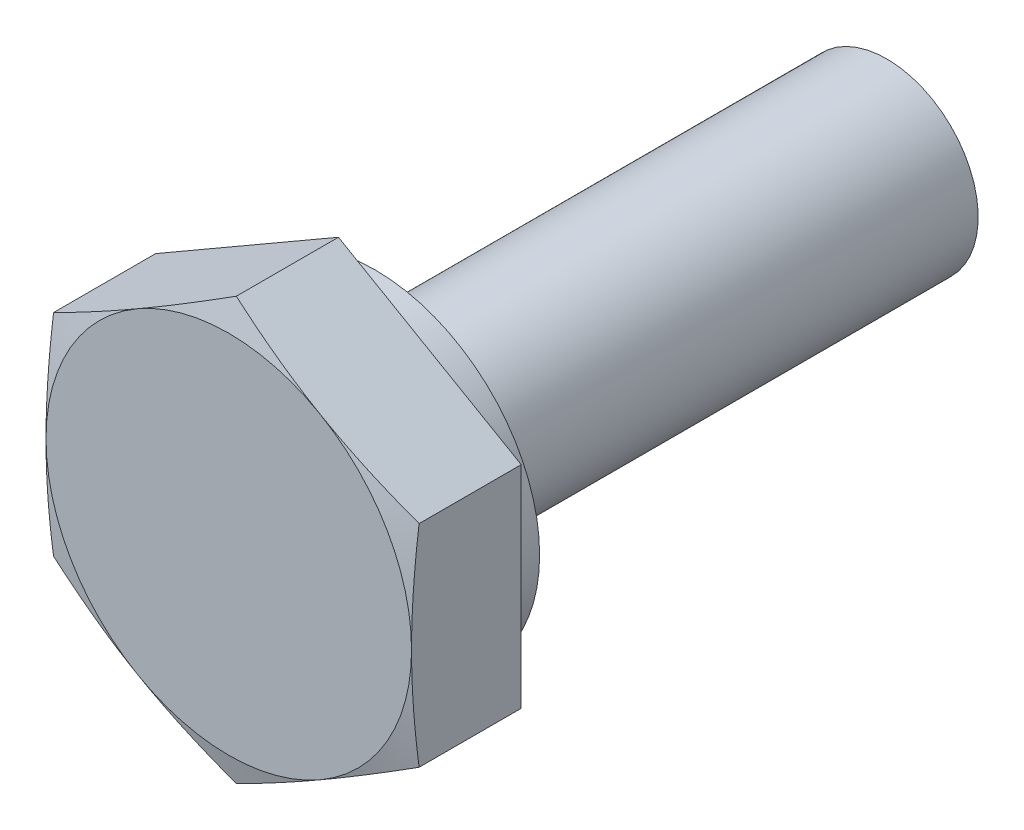
SolidWorks part; units mm, degrees
ref_plane "Plano frontal" through (0, 0, 0) normal (0, 0, 1) x (1, 0, 0)
ref_plane "Plano superior" through (0, 0, 0) normal (0, 1, 0) x (1, 0, 0)
ref_plane "Plano direito" through (0, 0, 0) normal (1, 0, 0) x (0, 0, -1)
sketch "Esboço1" plane through (0, 0, 0) normal (0, 0, 1) x (1, 0, 0)
  line L1 (0, 5.7735) -> (-5, 2.8868)
  line L2 (-5, 2.8868) -> (-5, -2.8868)
  line L3 (-5, -2.8868) -> (0, -5.7735)
  line L4 (0, -5.7735) -> (5, -2.8868)
  line L5 (5, -2.8868) -> (5, 2.8868)
  line L6 (5, 2.8868) -> (0, 5.7735)
  circle A0 centre (0, 0) radius 5 construction
  dimension "D1" = 10
extrude "Ressalto-extrusão3" add sketch "Esboço1" along normal blind 4
sketch "Esboço5" plane through (0, 0, 4) normal (0, 0, 1) x (1, 0, 0)
  circle A0 centre (-0.126, 0) radius 5.563
extrude "Corte-extrusão4" cut sketch "Esboço5" against normal blind 13 draft 75 flip side to cut
sketch "Esboço6" plane through (0, 0, 0) normal (0, 0, -1) x (-1, 0, 0)
  circle A0 centre (0, 0) radius 5.4673
extrude "Corte-extrusão5" cut sketch "Esboço6" against normal blind 13 draft 75 flip side to cut
sketch "Esboço7" plane through (0, 0, 0) normal (0, 0, -1) x (-1, 0, 0)
  circle A0 centre (0, 0) radius 2.5
  dimension "D1" = 5
extrude "Ressalto-extrusão4" add sketch "Esboço7" along normal blind 14 separate body
cosmetic thread "Representação de rosca1" parameters "D2"=4.11
sketch "Esboço8" plane through (0, 0, 4) normal (0, 0, 1) x (1, 0, 0)
  line L0 (4.4017, 3.2322) -> (0.4093, 5.5372) construction
  circle A0 centre (0, 0) radius 5
extrude "Corte-extrusão6" cut sketch "Esboço8" against normal blind 15 draft 75 flip side to cut
sketch "Esboço9" plane through (0, 0, 0) normal (0, 0, -1) x (-1, 0, 0)
  circle A0 centre (0, 0) radius 4.5031
extrude "Corte-extrusão7" cut sketch "Esboço9" against normal blind 1 flip side to cut
